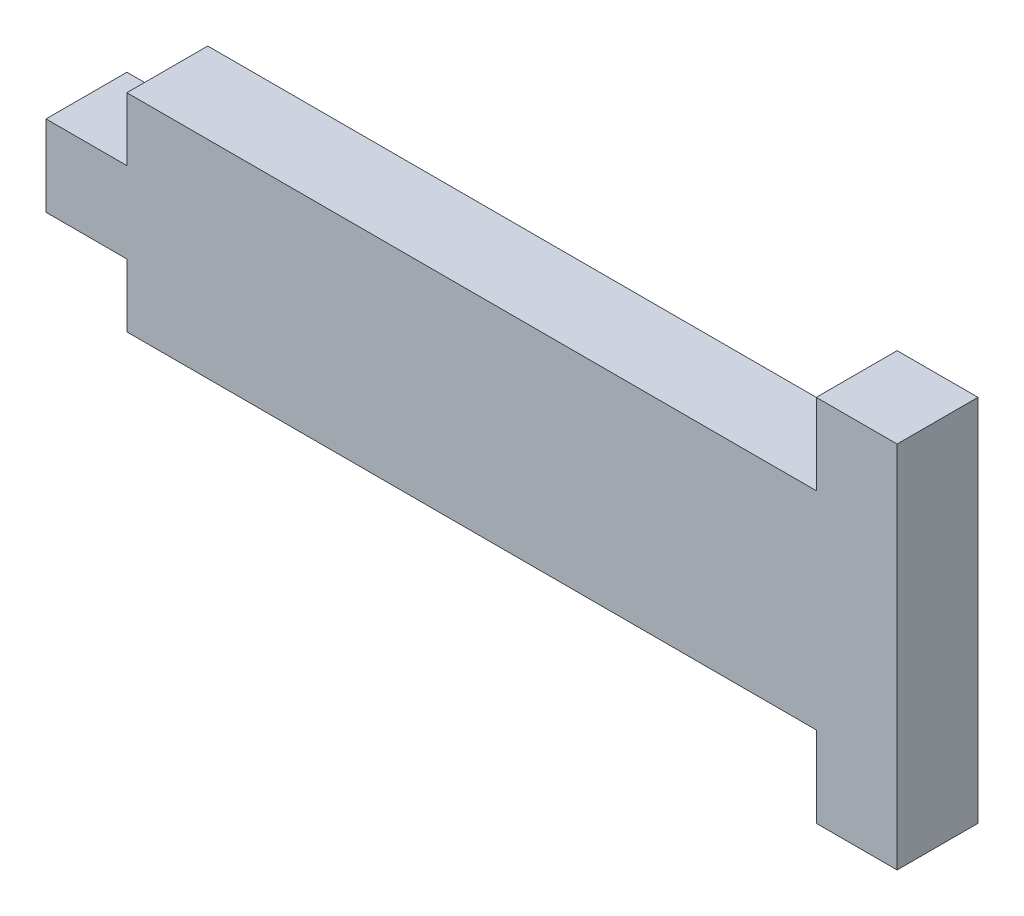
SolidWorks part; units mm, degrees
ref_plane "Front Plane" through (0, 0, 0) normal (0, 0, 1) x (1, 0, 0)
ref_plane "Top Plane" through (0, 0, 0) normal (0, 1, 0) x (1, 0, 0)
ref_plane "Right Plane" through (0, 0, 0) normal (1, 0, 0) x (0, 0, -1)
sketch "Sketch1" plane through (0, 0, 0) normal (0, 0, 1) x (1, 0, 0)
  line L0 (25.0625, 0) -> (20.3, 0) construction
  line L1 (20.3, 0) -> (20.3, -4.7625) construction
  line L2 (20.3, -4.7625) -> (25.0625, -4.7625) construction
  line L3 (25.0625, -4.7625) -> (25.0625, 0) construction
  line L4 (20.3, 12.2) -> (20.3, 0) construction
  line L5 (20.3, 0) -> (25.0625, 0) construction
  line L6 (25.0625, 0) -> (25.0625, 12.2) construction
  line L7 (25.0625, 12.2) -> (20.3, 12.2) construction
  line L8 (25.0625, 16.9625) -> (20.3, 16.9625) construction
  line L9 (20.3, 16.9625) -> (20.3, 12.2) construction
  line L10 (20.3, 12.2) -> (25.0625, 12.2) construction
  line L11 (25.0625, 12.2) -> (25.0625, 16.9625) construction
  line L12 (-20.3, 0) -> (20.3, 0) construction
  line L13 (20.3, 0) -> (20.3, 12.2) construction
  line L14 (20.3, 12.2) -> (-20.3, 12.2) construction
  line L15 (-20.3, 12.2) -> (-20.3, 0) construction
  line L16 (25.0625, 0) -> (20.3, 0)
  line L17 (20.3, 0) -> (20.3, -4.7625)
  line L18 (20.3, -4.7625) -> (25.0625, -4.7625)
  line L19 (25.0625, -4.7625) -> (25.0625, 0)
  line L20 (20.3, 12.2) -> (20.3, 0)
  line L21 (20.3, 0) -> (25.0625, 0)
  line L22 (25.0625, 0) -> (25.0625, 12.2)
  line L23 (25.0625, 12.2) -> (20.3, 12.2)
  line L24 (25.0625, 16.9625) -> (20.3, 16.9625)
  line L25 (20.3, 16.9625) -> (20.3, 12.2)
  line L26 (20.3, 12.2) -> (25.0625, 12.2)
  line L27 (25.0625, 12.2) -> (25.0625, 16.9625)
  line L28 (-20.3, 0) -> (20.3, 0)
  line L29 (20.3, 0) -> (20.3, 12.2)
  line L30 (20.3, 12.2) -> (-20.3, 12.2)
  line L31 (-20.3, 12.2) -> (-20.3, 0)
  line L33 (-25.0625, 8.4813) -> (-15.5375, 8.4813)
  line L34 (-25.0625, 8.4813) -> (-25.0625, 3.7188)
  line L35 (-25.0625, 3.7188) -> (-15.5375, 3.7188)
  line L36 (-15.5375, 8.4813) -> (-15.5375, 3.7188)
  line L37 (-25.0625, 8.4813) -> (-15.5375, 3.7188) construction
  line L38 (-25.0625, 3.7188) -> (-15.5375, 8.4813) construction
  point P2 (-20.3, 6.1)
  dimension "D1" = 4.7625
  dimension "D2" = 4.7625
extrude "Boss-Extrude1" add sketch "Sketch1" along normal blind 4.7625 contours L33 L36 L35 L31 L28 L20 L30 | L23 L27 L24 L25 | L22 L23 L20 L16 | L18 L19 L16 L17
